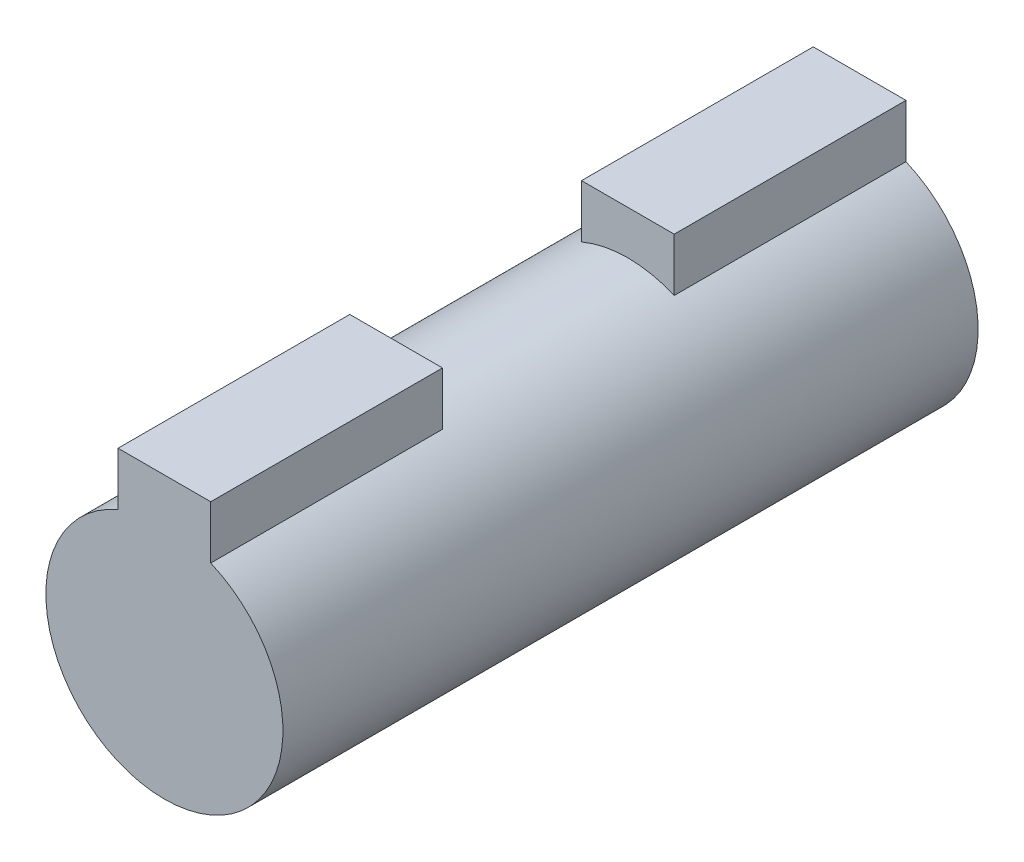
SolidWorks part; units mm, degrees
ref_plane "Front Plane" through (0, 0, 0) normal (0, 0, 1) x (1, 0, 0)
ref_plane "Top Plane" through (0, 0, 0) normal (0, 1, 0) x (1, 0, 0)
ref_plane "Right Plane" through (0, 0, 0) normal (1, 0, 0) x (0, 0, -1)
sketch "Sketch1" plane through (0, 0, 0) normal (0, 0, 1) x (1, 0, 0)
  line L0 (0, 0) -> (0, 9.6715) construction
  line L2 (-2, 7) -> (2, 7)
  line L3 (-2, 7) -> (-2, 4.7078)
  line L5 (2, 7) -> (2, 4.7078)
  arc A0 (-2, 4.7078) -> (2, 4.7078) centre (0, 0) ccw
  dimension "D1" = 10.23
  dimension "D2" = 4
  dimension "D3" = 7
extrude "Boss-Extrude1" add sketch "Sketch1" along normal blind 30
sketch "Sketch2" plane through (0, 0, 30) normal (0, 0, 1) x (1, 0, 0)
  circle A0 centre (0, 0) radius 5.115
  circle A1 centre (0, 0) radius 7.6322
extrude "Cut-Extrude3" cut sketch "Sketch2" against normal blind 10 from offset 10
